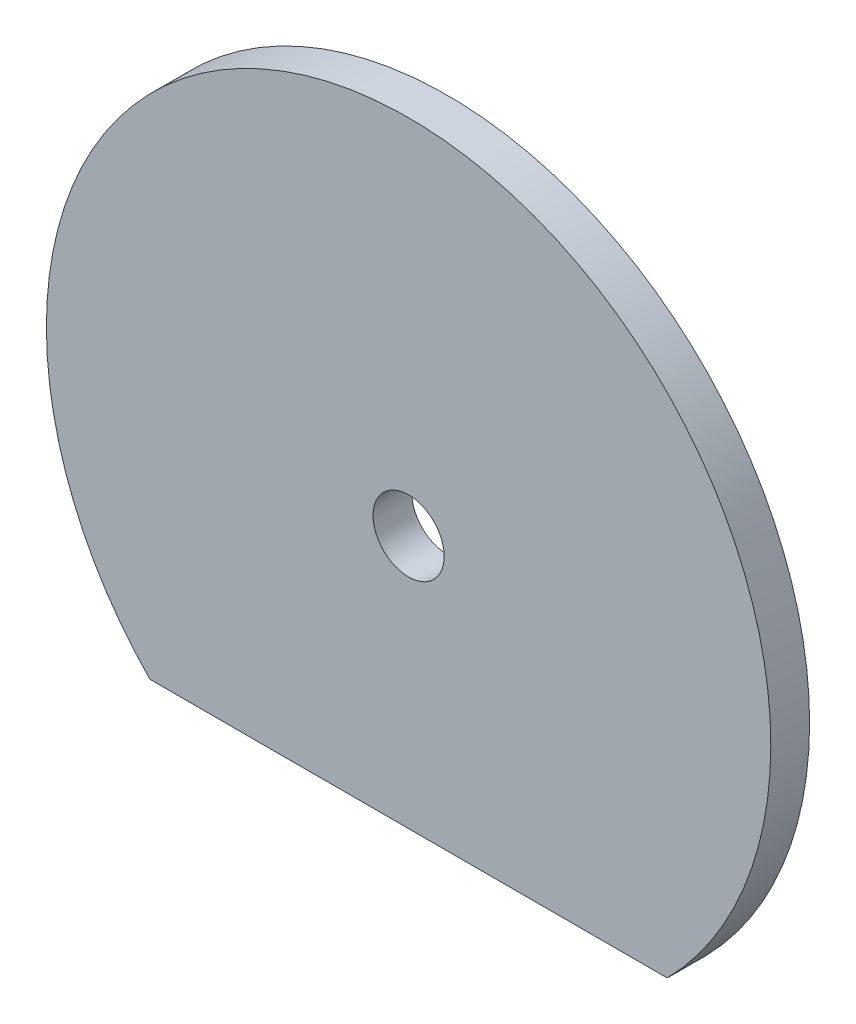
SolidWorks part; units mm, degrees
ref_plane "Front Plane" through (0, 0, 0) normal (0, 0, 1) x (1, 0, 0)
ref_plane "Top Plane" through (0, 0, 0) normal (0, 1, 0) x (1, 0, 0)
ref_plane "Right Plane" through (0, 0, 0) normal (1, 0, 0) x (0, 0, -1)
sketch "Sketch1" plane through (0, 0, 0) normal (0, 0, 1) x (1, 0, 0)
  line L0 (0, 0) -> (40, 0)
  arc A0 (40, 0) -> (0, 0) centre (20, 19.5959) ccw
  dimension "D1" = 28
  dimension "D2" = 40
extrude "Boss-Extrude1" add sketch "Sketch1" along normal blind 3
sketch "Sketch2" plane through (0, 0, 3) normal (0, 0, 1) x (1, 0, 0)
  circle A0 centre (20, 19.5959) radius 2.75
  dimension "D1" = 5.5
extrude "Cut-Extrude1" cut sketch "Sketch2" against normal blind 10
